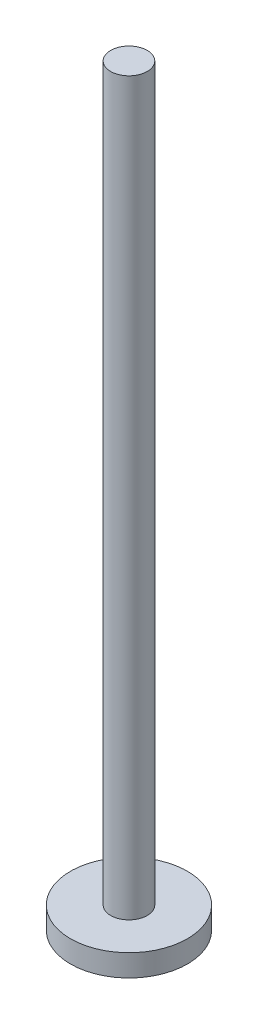
SolidWorks part; units mm, degrees
material "6061-T6 (SS)"
ref_plane "前视基准面" through (0, 0, 0) normal (0, 0, 1) x (1, 0, 0)
ref_plane "上视基准面" through (0, 0, 0) normal (0, 1, 0) x (1, 0, 0)
ref_plane "右视基准面" through (0, 0, 0) normal (1, 0, 0) x (0, 0, -1)
sketch "草图1" plane through (0, 0, 0) normal (0, 1, 0) x (1, 0, 0)
  circle A0 centre (0, 0) radius 8
  dimension "D1" = 16
extrude "凸台-拉伸1" add sketch "草图1" along normal blind 3
sketch "草图2" plane through (0, 3, 0) normal (0, 1, 0) x (1, 0, 0)
  circle A0 centre (0, 0) radius 2.5
  dimension "D1" = 5
extrude "凸台-拉伸2" add sketch "草图2" along normal blind 100
equation "\"行程L\"= 50"
equation "\"D1@凸台-拉伸2\"=\"行程L\"+50"
